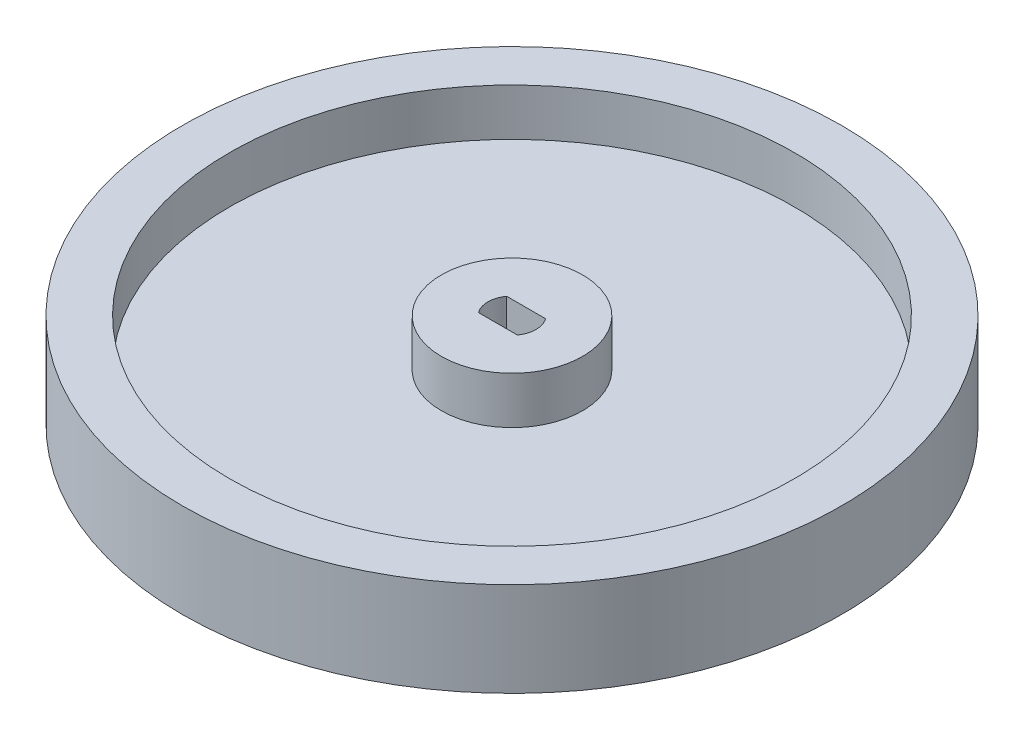
SolidWorks part; units mm, degrees
ref_plane "Ön Düzlem" through (0, 0, 0) normal (0, 0, 1) x (1, 0, 0)
ref_plane "Üst Düzlem" through (0, 0, 0) normal (0, 1, 0) x (1, 0, 0)
ref_plane "Sağ Düzlem" through (0, 0, 0) normal (1, 0, 0) x (0, 0, -1)
sketch "Çizim1" plane through (0, 0, 0) normal (0, 1, 0) x (1, 0, 0)
  circle A0 centre (0, 0) radius 35
extrude "Yükseklik-Ekstrüzyon1" add sketch "Çizim1" along normal blind 5
sketch "Çizim2" plane through (0, 5, 0) normal (0, 1, 0) x (1, 0, 0)
  line L1 (-2.0622, 1.5) -> (2.0622, 1.5)
  line L3 (-2.0622, -1.5) -> (2.0622, -1.5)
  circle A0 centre (0, 0) radius 7.5
  arc A1 (-2.0622, 1.5) -> (-2.0622, -1.5) centre (0, 0) ccw
  arc A2 (2.0622, -1.5) -> (2.0622, 1.5) centre (0, 0) ccw
  dimension "D1" = 15
extrude "Yükseklik-Ekstrüzyon2" add sketch "Çizim2" along normal blind 5
sketch "Çizim3" plane through (0, 5, 0) normal (0, 1, 0) x (1, 0, 0)
  line L0 (-2.0622, 1.5) -> (2.0622, 1.5)
  line L1 (-2.0622, -1.5) -> (2.0622, -1.5)
  arc A0 (-2.0622, 1.5) -> (-2.0622, -1.5) centre (0, 0) ccw
  arc A1 (2.0622, -1.5) -> (2.0622, 1.5) centre (0, 0) ccw
extrude "Kes-Ekstrüzyon1" cut sketch "Çizim3" against normal blind 4
sketch "Çizim4" plane through (0, 1, 0) normal (0, 1, 0) x (1, 0, 0)
  circle A0 centre (0, 0) radius 1.5
extrude "Kes-Ekstrüzyon2" cut sketch "Çizim4" against normal blind 4
sketch "Çizim5" plane through (0, 5, 0) normal (0, 1, 0) x (1, 0, 0)
  circle A0 centre (0, 0) radius 35
  circle A1 centre (0, 0) radius 30
extrude "Yükseklik-Ekstrüzyon3" add sketch "Çizim5" along normal blind 5
